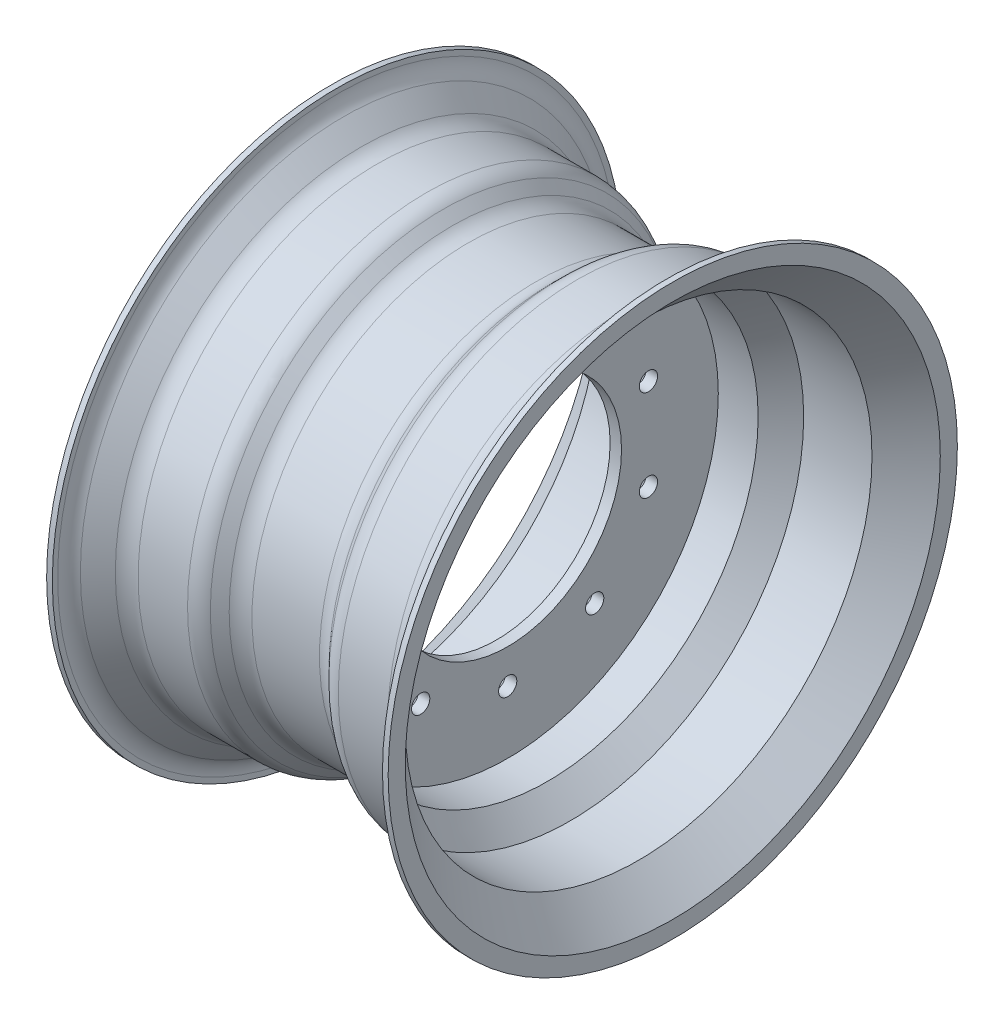
SolidWorks part; units mm, degrees
ref_plane "Front Plane" through (0, 0, 0) normal (0, 0, 1) x (1, 0, 0)
ref_plane "Top Plane" through (0, 0, 0) normal (0, 1, 0) x (1, 0, 0)
ref_plane "Right Plane" through (0, 0, 0) normal (1, 0, 0) x (0, 0, -1)
sketch "Sketch1" plane through (0, 0, 0) normal (0, 0, 1) x (1, 0, 0)
  line L0 (0, 242.0289) -> (0, 0) construction
  line L1 (0, 0) -> (-543.0523, 0) construction
  line L2 (-150, 235) -> (-120, 205)
  line L3 (-120, 205) -> (-60, 205)
  line L4 (-60, 205) -> (-40, 185)
  line L5 (-40, 185) -> (-5, 185)
  line L6 (-150, 235) -> (-150, 250)
  line L7 (150, 235) -> (150, 250)
  line L8 (60, 205) -> (40, 185)
  line L9 (120, 205) -> (60, 205)
  line L10 (150, 235) -> (120, 205)
  line L11 (-145, 237.0711) -> (-145, 250)
  line L12 (-145, 237.0711) -> (-117.9289, 210)
  line L13 (-117.9289, 210) -> (-57.9289, 210)
  line L14 (-57.9289, 210) -> (-37.9289, 190)
  line L15 (-37.9289, 190) -> (37.9289, 190)
  line L16 (57.9289, 210) -> (37.9289, 190)
  line L17 (117.9289, 210) -> (57.9289, 210)
  line L18 (145, 237.0711) -> (117.9289, 210)
  line L19 (145, 237.0711) -> (145, 250)
  line L20 (-150, 250) -> (-145, 250)
  line L21 (145, 250) -> (150, 250)
  line L22 (5, 185) -> (40, 185)
  line L24 (-5, 185) -> (-5, 100)
  line L25 (-5, 100) -> (5, 100)
  line L26 (5, 185) -> (5, 100)
  line L27 (-40, 185) -> (40, 185) construction
  point P12 (0, 185)
  dimension "D1" = 250
  dimension "D2" = 15
  dimension "D3" = 30
  dimension "D4" = 60
  dimension "D5" = 20
  dimension "D6" = 40
  dimension "D7" = 135
  dimension "D8" = 135
  dimension "D9" = 5
  dimension "D10" = 10
  dimension "D11" = 5
  dimension "D12" = 100
revolve "Revolve1" add sketch "Sketch1" angle 360 about L1
fillet "Fillet1" radius 20 8 edges at (145, 0, -237.0711) (117.9289, 0, -210) (57.9289, 0, -210) (37.9289, 0, -190) (-37.9289, 0, -190) (-57.9289, 0, -210) (-117.9289, 0, -210) (-145, 0, -237.0711)
sketch "Sketch2" plane through (5, 0, 0) normal (1, 0, 0) x (0, 0, -1)
  circle A0 centre (0, 130) radius 8
  point P2 (0, 0)
  dimension "D2" = 16
  dimension "D1" = 130
extrude "Cut-Extrude2" cut sketch "Sketch2" against normal blind 10
pattern_circular "CirPattern1" count 10 over 360 about axis through (0, 0, 0) along (1, 0, 0) of "Cut-Extrude2"
